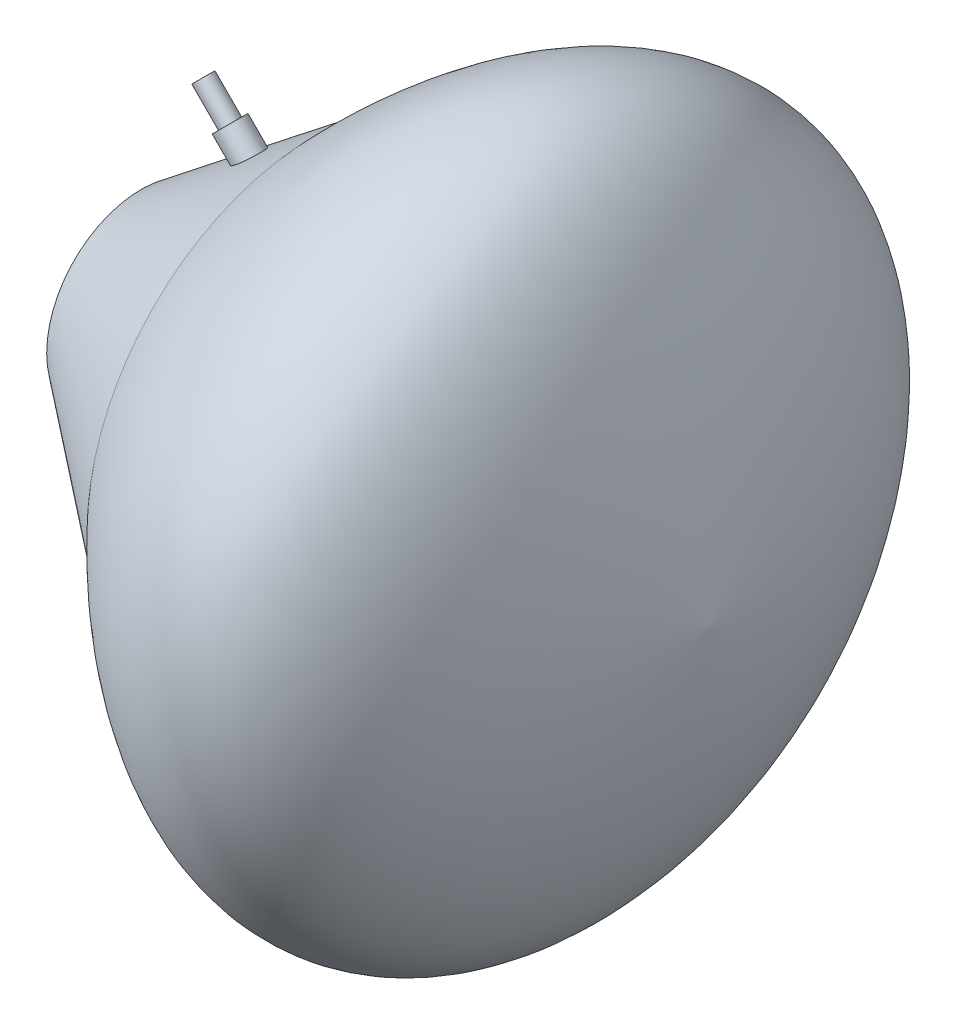
SolidWorks part; units mm, degrees
material "ABS PC"
ref_plane "Alzado" through (0, 0, 0) normal (0, 0, 1) x (1, 0, 0)
ref_plane "Planta" through (0, 0, 0) normal (0, 1, 0) x (1, 0, 0)
ref_plane "Vista lateral" through (0, 0, 0) normal (1, 0, 0) x (0, 0, -1)
sketch "Croquis1" plane through (0, 0, 0) normal (1, 0, 0) x (0, 0, -1)
  line L0 (0, -25) -> (0, 25) construction
  line L2 (0, 55) -> (0, -55) construction
  point P8 (0, 0)
  dimension "D1" = 50
sketch "Croquis2" plane through (0, 0, 0) normal (0, 0, 1) x (1, 0, 0)
  line L0 (0, 0) -> (0, 25)
  line L1 (0, -25) -> (0, 25) construction
  line L2 (0, 25) -> (46.0596, 60.3594)
  line L3 (0, 0) -> (150.1705, 0)
  line L4 (55, 0) -> (-55, 0) construction
  spline S0 degree 2 poles (46.0596, 60.3594) (127.9578, 146.6653) (150.1705, 0) knots 0 0 0 1 1 1
revolve "Revolución1" add sketch "Croquis2" angle 360 about L3
ref_plane "Plano1" through (0, 0, 0) normal (-0.7071, 0.7071, 0) x (0.7071, 0.7071, 0)
sketch "Croquis3" plane through (0, 0, 0) normal (-0.7071, 0.7071, 0) x (0.7071, 0.7071, 0)
  line L0 (-82.5938, 0) -> (82.5938, 0) construction
  circle A0 centre (53.2182, 0) radius 2.5
  dimension "D1" = 5
extrude "Saliente-Extruir1" add sketch "Croquis3" along normal blind 30
sketch "Croquis4" plane through (0, 0, 0) normal (-0.7071, 0.7071, 0) x (0.7071, 0.7071, 0)
  circle A0 centre (53.2182, 0) radius 3.861
extrude "Saliente-Extruir2" add sketch "Croquis4" along normal blind 20
